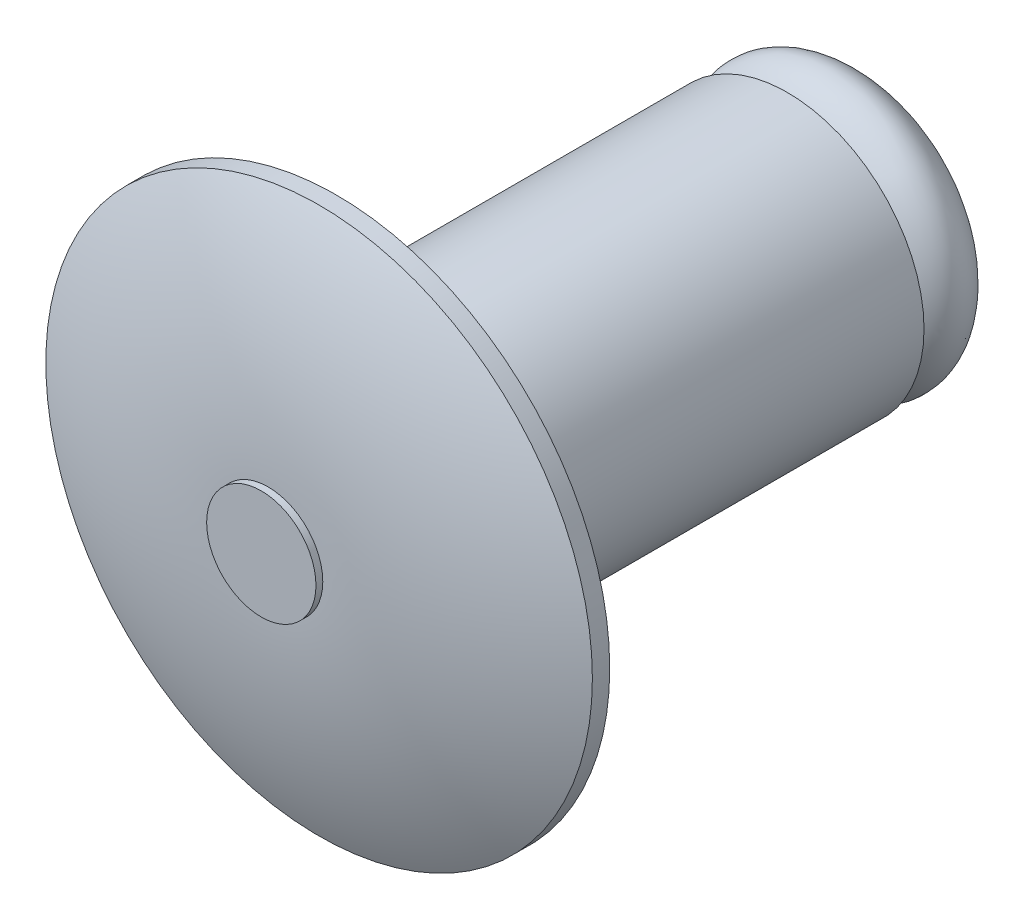
SolidWorks part; units mm, degrees
material "1023 Carbon Steel Sheet (SS)"
ref_plane "Front" through (0, 0, 0) normal (0, 0, 1) x (1, 0, 0)
ref_plane "Top" through (0, 0, 0) normal (0, 1, 0) x (1, 0, 0)
ref_plane "Right" through (0, 0, 0) normal (1, 0, 0) x (0, 0, -1)
sketch "Sketch1" plane through (0, 0, 0) normal (1, 0, 0) x (0, 0, -1)
  line L0 (-10.9, 0) -> (-1, 0) construction
  line L1 (-1, 0) -> (0, 0) construction
  line L2 (0, 0) -> (6.6, 0) construction
  line L3 (6.6, 0) -> (8.1, 0) construction
  line L4 (6.6, 2.05) -> (6.6, -2.05) construction
  line L5 (6.6, 2) -> (6.6, -2) construction
  line L8 (0, 4) -> (0, -4) construction
  line L9 (6.6, 2) -> (6.6, -2) construction
  point P7 (3, 0)
  dimension "Head Height" = 1
  dimension "D5" = 1.5
  dimension "D9" = 9.9
  dimension "Head Diameter" = 8
  dimension "Diameter" = 4
  dimension "Length" = 6.6
  dimension "For Material Thickness" = 3
  dimension "For Hole Size" = 4.1
  dimension "For Drill Bit Size" = 4
sketch "Sketch2" plane through (0, 0, 0) normal (1, 0, 0) x (0, 0, -1)
  line L0 (-10.9, 0) -> (-10.9, 0.8)
  line L1 (-10.9, 0.8) -> (0, 0.8) construction
  line L2 (0, 4) -> (0, -4) construction
  line L3 (0, 0) -> (0, 4) construction
  line L4 (-1, 0) -> (-1, -1.8472) construction
  line L5 (6.6, 2) -> (0, 2)
  line L6 (6.6, 2) -> (6.6, 1.5) construction
  line L7 (8.1, 0) -> (8.1, 2) construction
  line L8 (6.6, 2) -> (6.6, 1.5)
  line L9 (8.1, 2) -> (6.6, 2) construction
  line L10 (6.6, 0) -> (8.1, 0) construction
  line L11 (6.6, 0) -> (8.1, 0)
  line L12 (-10.9, 0) -> (6.6, 0)
  line L13 (-1, 0.8) -> (-1, 0) construction
  line L14 (6.6, 2) -> (6.6, 0) construction
  line L15 (6.6, 2) -> (6.6, 1.5) construction
  line L16 (6.6, 1.5) -> (6.6, 1) construction
  line L17 (6.6, 1) -> (6.6, 0.5) construction
  line L18 (6.6, 0.5) -> (6.6, 0) construction
  line L19 (0, 2) -> (0, 4)
  line L20 (-1, 0.8) -> (-10.9, 0.8)
  line L22 (0, 4) -> (-0.254, 4)
  arc A2 (-0.254, 4) -> (-1, 0.8) centre (6.2363, 0.8) ccw
  ellipse E0 centre (7.1972, 0) end of major axis (7.1972, 2) minor radius 0.9028 (8.1, 0) -> (6.6, 1.5) ccw
  dimension "D1" = 0.8
  dimension "D2" = 2
  dimension "D3" = 0.254
revolve "Revolve1" add sketch "Sketch2" angle 360 about L12
sketch "Sketch3" plane through (0, 0, 0) normal (0, 1, 0) x (1, 0, 0)
  line L0 (0, -10.9) -> (1.0032, -9.5926)
  line L1 (-0.8, -10.9) -> (0.8, -10.9) construction
  line L3 (0, -10.9) -> (0, -11.408) construction
  line L4 (0, -10.9) -> (-1.0032, -9.5926)
  line L5 (-1.0032, -9.5926) -> (-1.0032, -11.408)
  line L6 (-1.0032, -11.408) -> (1.0032, -11.408)
  line L7 (1.0032, -11.408) -> (1.0032, -9.5926)
  dimension "D1" = 75
  dimension "D2" = 0.2032
  dimension "D3" = 0.508
extrude "Cut-Extrude1" cut sketch "Sketch3" against normal through all both and the other way through all
sketch "Sketch4" plane through (0, 0, 0) normal (1, 0, 0) x (0, 0, -1)
  line L0 (-10.9, 0) -> (-11.408, 0) construction
  line L1 (-10.9, -0.8) -> (-10.9, 0.8) construction
  line L2 (-11.154, 0) -> (-9.846, 1.308)
  line L3 (-11.154, 0) -> (-9.846, -1.308)
  line L4 (-9.846, 1.308) -> (-11.408, 1.308)
  line L5 (-11.408, 1.308) -> (-11.408, -1.308)
  line L6 (-11.408, -1.308) -> (-9.846, -1.308)
  dimension "D1" = 0.508
  dimension "D2" = 0.508
  dimension "D3" = 90
extrude "Cut-Extrude2" cut sketch "Sketch4" against normal through all both and the other way through all
fillet "Fillet2" radius 0.254 1 edges at (2, 0, 0)
ref_plane "Plane1" through (0, 0, 1.1) normal (0, 0, -1) x (-1, 0, 0)
sketch "Sketch5" plane through (0, 0, 1.1) normal (0, 0, -1) x (-1, 0, 0)
  circle A0 centre (0, 0) radius 1.2114
  dimension "D1" = 2.4229
extrude "Cut-Extrude3" cut sketch "Sketch5" against normal blind 10
equation "\"D5@Sketch1\" = \"Head Height@Sketch1\" * 1.5"
equation "\"D9@Sketch1\"= \"Length@Sketch1\" * 1.5"
